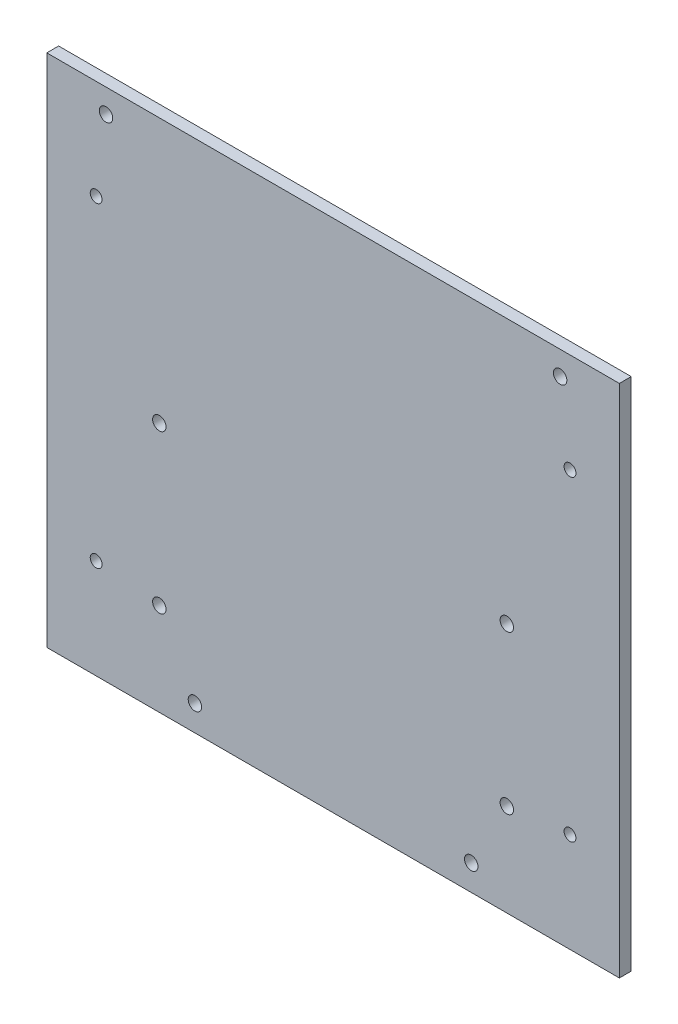
SolidWorks part; units mm, degrees
ref_plane "Front Plane" through (0, 0, 0) normal (0, 0, 1) x (1, 0, 0)
ref_plane "Top Plane" through (0, 0, 0) normal (0, 1, 0) x (1, 0, 0)
ref_plane "Right Plane" through (0, 0, 0) normal (1, 0, 0) x (0, 0, -1)
sketch "Sketch1" plane through (0, 0, 0) normal (0, 0, 1) x (1, 0, 0)
  line L0 (-71.9, 130.4) -> (-75.9, 130.4) construction
  line L1 (-72.5, 0) -> (72.5, 0)
  line L2 (-72.5, 0) -> (-72.5, 130.4)
  line L3 (-72.5, 130.4) -> (72.5, 130.4)
  line L4 (72.5, 0) -> (72.5, 130.4)
  line L5 (0, 0) -> (0, 130.4) construction
  line L7 (-60, 25.2) -> (60, 25.2) construction
  line L8 (-60, 25.2) -> (-60, 105.2) construction
  line L9 (-60, 105.2) -> (60, 105.2) construction
  line L10 (60, 25.2) -> (60, 105.2) construction
  line L11 (-60, 25.2) -> (60, 105.2) construction
  line L12 (-60, 105.2) -> (60, 25.2) construction
  circle A0 centre (-56.5, 6.5) radius 1.7 construction
  circle A1 centre (56.5, 6.5) radius 1.7 construction
  circle A2 centre (-60, 105.2) radius 1.5
  circle A3 centre (60, 105.2) radius 1.5
  circle A4 centre (60, 25.2) radius 1.5
  circle A5 centre (-60, 25.2) radius 1.5
  point P7 (0, 65.2)
  dimension "D2" = 3.4
  dimension "D3" = 16
  dimension "D4" = 6.5
  dimension "D5" = 145
  dimension "D1" = 3
  dimension "D6" = 120
  dimension "D7" = 80
extrude "Boss-Extrude1" add sketch "Sketch1" along normal blind 3
sketch "Sketch3" plane through (0, 0, 3) normal (0, 0, 1) x (1, 0, 0)
  circle A0 centre (-57.5, 124.4) radius 1.7
  circle A1 centre (57.5, 124.4) radius 1.7
  circle A2 centre (-44, 63.4388) radius 1.7
  circle A3 centre (-44, 23.4388) radius 1.7
  circle A4 centre (44, 23.4388) radius 1.7
  circle A5 centre (44, 63.4388) radius 1.7
  circle A6 centre (-34.9875, 6.5) radius 1.7
  circle A7 centre (34.9875, 6.5) radius 1.7
  dimension "D1" = 3.4
  dimension "D2" = 3.4
  dimension "D3" = 3.4
extrude "dependent_holes" cut sketch "Sketch3" against normal blind 10
